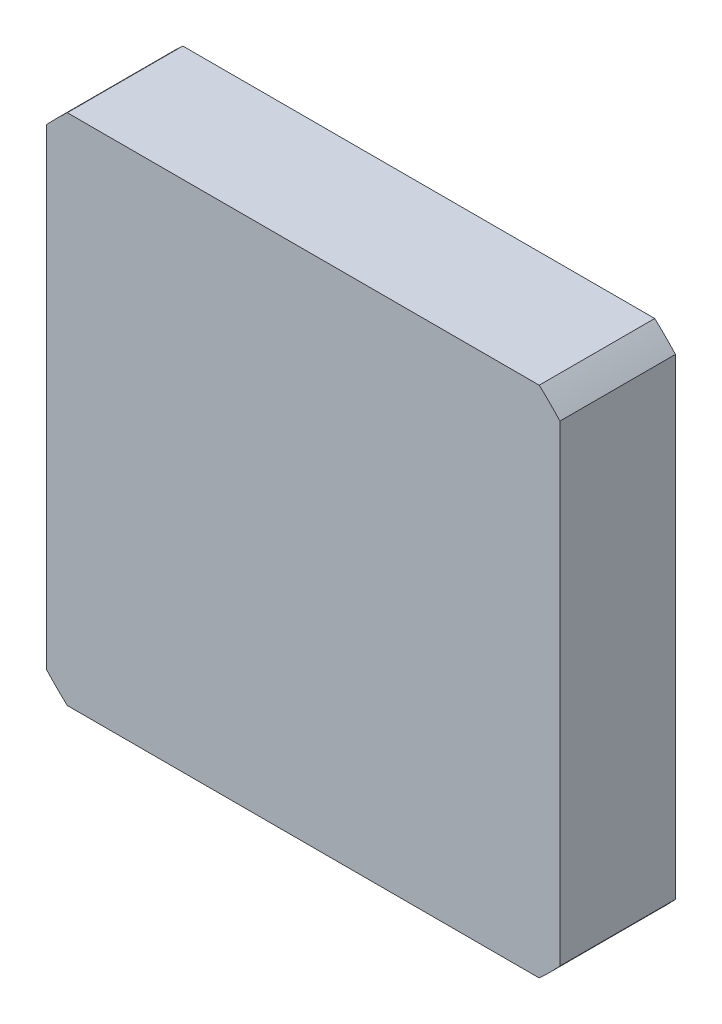
SolidWorks part; units mm, degrees
ref_plane "Front Plane" through (0, 0, 0) normal (0, 0, 1) x (1, 0, 0)
ref_plane "Top Plane" through (0, 0, 0) normal (0, 1, 0) x (1, 0, 0)
ref_plane "Right Plane" through (0, 0, 0) normal (1, 0, 0) x (0, 0, -1)
sketch "Sketch1" plane through (0, 0, 0) normal (0, 0, 1) x (1, 0, 0)
  line L1 (-60, 60) -> (60, 60)
  line L2 (-60, 60) -> (-60, -60)
  line L3 (-60, -60) -> (60, -60)
  line L4 (60, 60) -> (60, -60)
  line L5 (-60, 60) -> (60, -60) construction
  line L6 (-60, -60) -> (60, 60) construction
  line L8 (-60, 0) -> (60, 0) construction
  circle A0 centre (0, 0) radius 81.5
  point P0 (0, 0)
  dimension "D2" = 163
  dimension "D1" = 120
extrude "Boss-Extrude1" add sketch "Sketch1" along normal blind 27
